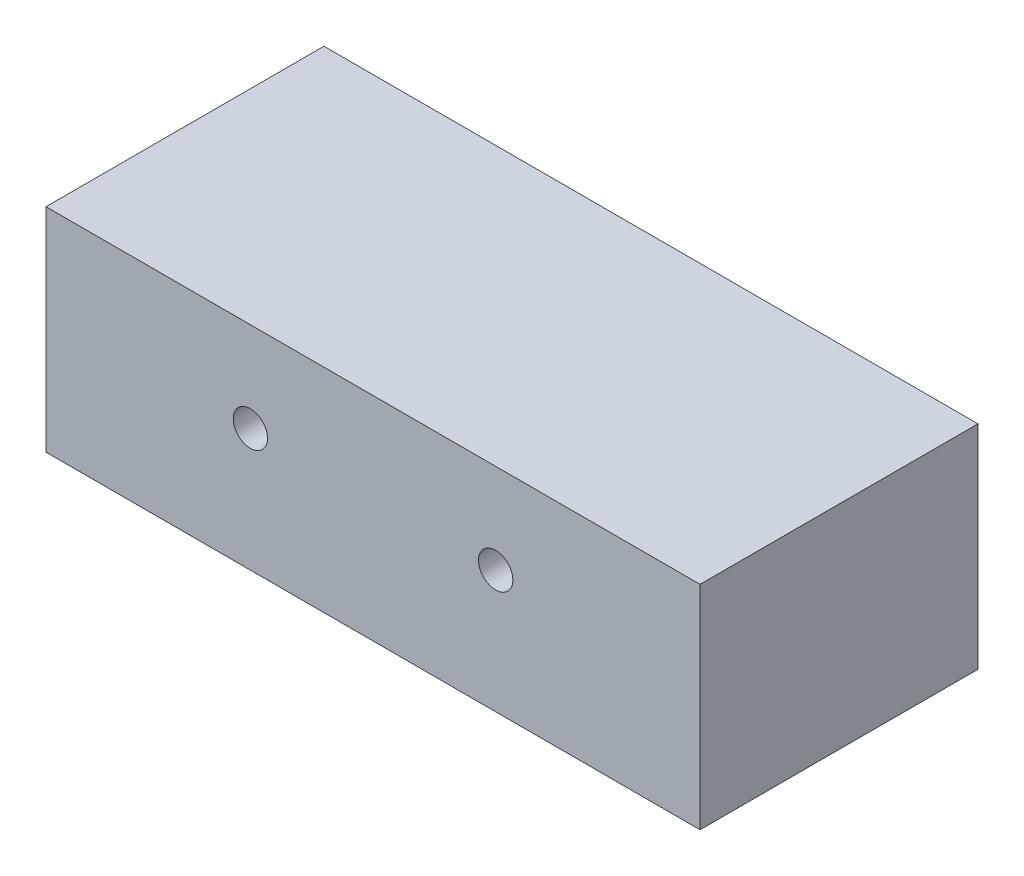
SolidWorks part; units mm, degrees
material "铝材"
ref_plane "前基準面" through (0, 0, 0) normal (0, 0, 1) x (1, 0, 0)
ref_plane "上基準面" through (0, 0, 0) normal (0, 1, 0) x (1, 0, 0)
ref_plane "右基準面" through (0, 0, 0) normal (1, 0, 0) x (0, 0, -1)
sketch "草图1" plane through (0, 0, 0) normal (0, 0, 1) x (1, 0, 0)
  line L1 (0, 0) -> (80, 0)
  line L2 (0, 0) -> (0, 26)
  line L3 (0, 26) -> (80, 26)
  line L4 (80, 0) -> (80, 26)
  dimension "D1" = 80
  dimension "D2" = 26
extrude "凸台-拉伸1" add sketch "草图1" along normal blind 34
hole_wizard "M5 螺纹孔1" positions "草图5" profile "草图4" tap size "M5" standard "ISO"
sketch "草图5" plane through (0, 0, 0) normal (0, 0, -1) x (-1, 0, 0)
  point P0 (-55, 15)
  point P1 (-25, 15)
sketch "草图4" plane through (55, 15, 0) normal (1, 0, 0) x (0, 1, 0)
  line L0 (0, 0) -> (0, 13.6618)
  line L1 (0, 13.6618) -> (2.1, 12.4)
  line L2 (2.1, 12.4) -> (2.1, 0)
  line L5 (2.1, 0) -> (0, 0)
  line L10 (0, 13.6618) -> (-2.1, 12.4) construction
  line L11 (0, -6.35) -> (0, 107.95) construction
  dimension "螺纹孔钻头直径" = 4.2
  dimension "螺纹孔钻头深度" = 12.4
  dimension "导头角度" = 118
cosmetic thread "孔螺蚊线3" parameters "D1"=10, "D2"=5
cosmetic thread "孔螺蚊线4" parameters "D1"=10, "D2"=5
hole_wizard "M5 螺纹孔2" positions "草图7" profile "草图6" tap size "M5" standard "ISO"
sketch "草图7" plane through (0, 0, 34) normal (0, 0, 1) x (1, 0, 0)
  point P0 (25, 15)
  point P4 (55, 15)
sketch "草图6" plane through (25, 15, 34) normal (1, 0, 0) x (0, -1, 0)
  line L0 (0, 0) -> (0, 13.6618)
  line L1 (0, 13.6618) -> (2.1, 12.4)
  line L2 (2.1, 12.4) -> (2.1, 0)
  line L5 (2.1, 0) -> (0, 0)
  line L10 (0, 13.6618) -> (-2.1, 12.4) construction
  line L11 (0, -6.35) -> (0, 107.95) construction
  dimension "螺纹孔钻头直径" = 4.2
  dimension "螺纹孔钻头深度" = 12.4
  dimension "导头角度" = 118
cosmetic thread "孔螺蚊线5" parameters "D1"=10, "D2"=5
cosmetic thread "孔螺蚊线6" parameters "D1"=10, "D2"=5
